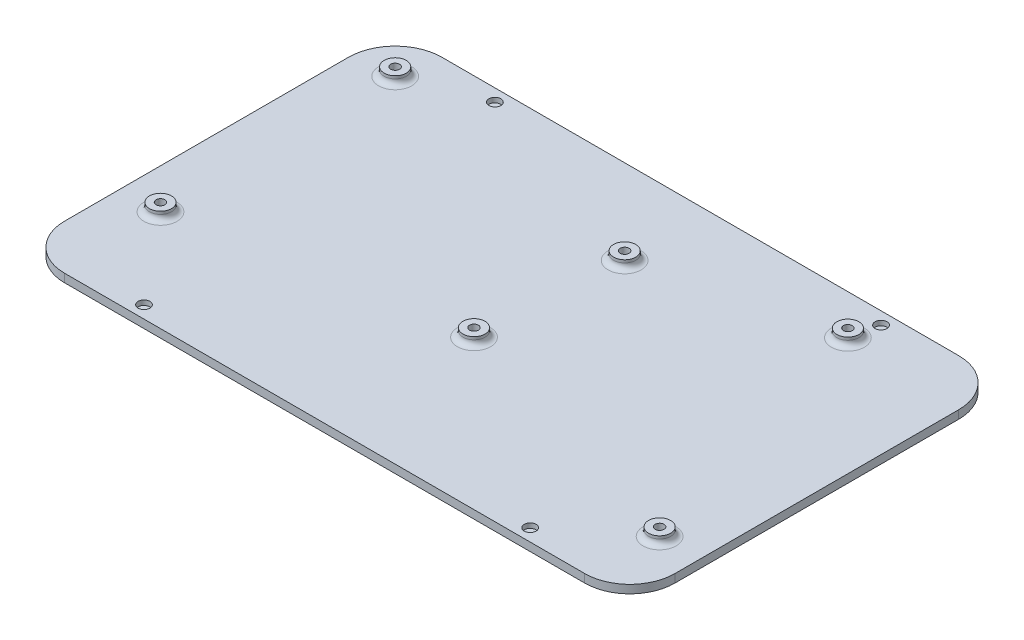
SolidWorks part; units mm, degrees
material "ABS"
ref_plane "Front Plane" through (0, 0, 0) normal (0, 0, 1) x (1, 0, 0)
ref_plane "Top Plane" through (0, 0, 0) normal (0, 1, 0) x (1, 0, 0)
ref_plane "Right Plane" through (0, 0, 0) normal (1, 0, 0) x (0, 0, -1)
sketch "Sketch1" plane through (0, 0, 0) normal (0, 1, 0) x (1, 0, 0)
  line L1 (0, 0) -> (-201.28, 0)
  line L2 (0, 0) -> (0, 116.21)
  line L3 (0, 116.21) -> (-201.28, 116.21)
  line L4 (-201.28, 0) -> (-201.28, 116.21)
  dimension "D1" = 201.28
  dimension "D2" = 116.21
extrude "Boss-Extrude1" add sketch "Sketch1" against normal blind 3
fillet "Fillet1" radius 6.98 2 edges at (0, -1.5, -116.21) (-201.28, -1.5, -116.21)
fillet "Fillet2" radius 6.35 2 edges at (0, -1.5, 0) (-201.28, -1.5, 0)
sketch "Sketch2" plane through (0, -3, 0) normal (0, -1, 0) x (-1, 0, 0)
  line L8 (6.35, -10) -> (194.93, -10)
  line L9 (-10, 109.23) -> (-10, 6.35)
  line L10 (194.3, 126.21) -> (6.98, 126.21)
  line L11 (211.28, 6.35) -> (211.28, 109.23)
  line L12 (6.35, -10) -> (194.93, -10)
  line L13 (-10, 109.23) -> (-10, 6.35)
  line L14 (194.3, 126.21) -> (6.98, 126.21)
  line L15 (211.28, 6.35) -> (211.28, 109.23)
  line L16 (6.35, 0) -> (194.93, 0)
  line L17 (0, 109.23) -> (0, 6.35)
  line L18 (194.3, 116.21) -> (6.98, 116.21)
  line L19 (201.28, 6.35) -> (201.28, 109.23)
  line L20 (6.35, 0) -> (194.93, 0)
  line L21 (0, 109.23) -> (0, 6.35)
  line L22 (194.3, 116.21) -> (6.98, 116.21)
  line L23 (201.28, 6.35) -> (201.28, 109.23)
  arc A8 (-10, 6.35) -> (6.35, -10) centre (6.35, 6.35) ccw
  arc A9 (6.98, 126.21) -> (-10, 109.23) centre (6.98, 109.23) ccw
  arc A10 (211.28, 109.23) -> (194.3, 126.21) centre (194.3, 109.23) ccw
  arc A11 (194.93, -10) -> (211.28, 6.35) centre (194.93, 6.35) ccw
  arc A12 (-10, 6.35) -> (6.35, -10) centre (6.35, 6.35) ccw
  arc A13 (6.98, 126.21) -> (-10, 109.23) centre (6.98, 109.23) ccw
  arc A14 (211.28, 109.23) -> (194.3, 126.21) centre (194.3, 109.23) ccw
  arc A15 (194.93, -10) -> (211.28, 6.35) centre (194.93, 6.35) ccw
  arc A16 (0, 6.35) -> (6.35, 0) centre (6.35, 6.35) ccw
  arc A17 (6.98, 116.21) -> (0, 109.23) centre (6.98, 109.23) ccw
  arc A18 (201.28, 109.23) -> (194.3, 116.21) centre (194.3, 109.23) ccw
  arc A19 (194.93, 0) -> (201.28, 6.35) centre (194.93, 6.35) ccw
  arc A20 (0, 6.35) -> (6.35, 0) centre (6.35, 6.35) ccw
  arc A21 (6.98, 116.21) -> (0, 109.23) centre (6.98, 109.23) ccw
  arc A22 (201.28, 109.23) -> (194.3, 116.21) centre (194.3, 109.23) ccw
  arc A23 (194.93, 0) -> (201.28, 6.35) centre (194.93, 6.35) ccw
  dimension "D1" = 10
  dimension "D2" = 0
extrude "Boss-Extrude3" add sketch "Sketch2" against normal up to surface (3 mm away) up to face at (-100.64, 0, -57.9801)
sketch "Sketch3" plane through (0, 0, 0) normal (0, 1, 0) x (1, 0, 0)
  line L0 (-100.64, -10) -> (-100.64, 126.21) construction
  line L1 (-6.35, -10) -> (-194.93, -10) construction
  line L2 (-194.3, 126.21) -> (-6.98, 126.21) construction
  line L3 (-211.28, 6.35) -> (-211.28, 109.23) construction
  line L6 (-100.64, 58.105) -> (-211.28, 58.105) construction
  line L7 (-100.64, -5.5) -> (-30.64, -5.5) construction
  circle A0 centre (-170.64, -5.5) radius 2.15
  circle A1 centre (-30.64, 121.71) radius 2.15
  circle A2 centre (-30.64, -5.5) radius 2.15
  circle A3 centre (-170.64, 121.71) radius 2.15
  dimension "D1" = 4.5
  dimension "D4" = 4.3
  dimension "D3" = 70
extrude "Cut-Extrude1" cut sketch "Sketch3" against normal blind 1.75
hole_wizard "M3 Clearance Hole2" positions "Sketch7" profile "Sketch5" hole size "M3" standard "ANSI Metric"
sketch "Sketch7" plane through (0, 0, 0) normal (0, 1, 0) x (1, 0, 0)
  point P0 (-196.83, 111.76)
  point P3 (-32.71, 111.76)
  point P6 (-97.45, 95.57)
  point P9 (-100.63, 44.13)
  point P12 (-4.45, 15.24)
  point P15 (-196.83, 26.67)
sketch "Sketch5" plane through (-196.83, 0, -111.76) normal (1, 0, 0) x (0, 0, 1)
  line L0 (1.6, 2) -> (0, 2)
  line L1 (0, 2) -> (0, 0)
  line L2 (1.6, 2) -> (1.6, 0)
  line L5 (1.6, 0) -> (0, 0)
  line L11 (0, -6.35) -> (0, 107.95) construction
  dimension "Hole Dia." = 3.2
  dimension "Hole Depth" = 2
sketch "Sketch8" plane through (0, 0, 0) normal (0, 1, 0) x (1, 0, 0)
  circle A0 centre (-196.83, 111.76) radius 4
  circle A1 centre (-196.83, 26.67) radius 4
  circle A2 centre (-100.63, 44.13) radius 4
  circle A3 centre (-4.45, 15.24) radius 4
  circle A4 centre (-97.45, 95.57) radius 4
  circle A5 centre (-32.71, 111.76) radius 4
  dimension "D1" = 8
extrude "Boss-Extrude4" add sketch "Sketch8" along normal blind 3
fillet "Fillet3" radius 2 6 edges at (-32.71, 0, -107.76) (-4.45, 0, -11.24) (-97.45, 0, -91.57) (-100.63, 0, -40.13) (-196.83, 0, -22.67) (-196.83, 0, -107.76)
hole_wizard "M3 Clearance Hole3" positions "Sketch10" profile "Sketch11" hole size "M3" standard "ANSI Metric"
sketch "Sketch10" plane through (0, 3, 0) normal (0, 1, 0) x (1, 0, 0)
  point P0 (-4.45, 15.24)
  point P3 (-32.71, 111.76)
  point P6 (-97.45, 95.57)
  point P9 (-100.63, 44.13)
  point P12 (-196.83, 111.76)
  point P15 (-196.83, 26.67)
sketch "Sketch11" plane through (-4.45, 3, -15.24) normal (1, 0, 0) x (0, 0, 1)
  line L0 (0, 0) -> (0, 3)
  line L1 (0, 3) -> (1.6, 3)
  line L2 (1.6, 3) -> (1.6, 0)
  line L5 (1.6, 0) -> (0, 0)
  line L11 (0, -6.35) -> (0, 107.95) construction
  dimension "Thru Hole Dia." = 3.2
  dimension "Thru Hole Depth" = 3
